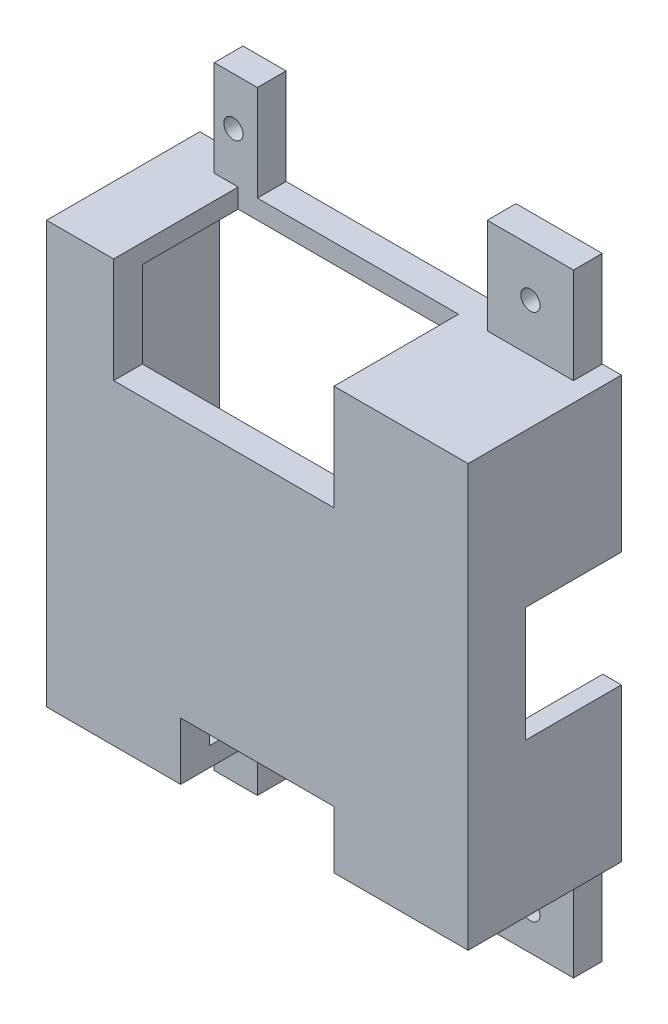
SolidWorks part; units mm, degrees
ref_plane "Front Plane" through (0, 0, 0) normal (0, 0, 1) x (1, 0, 0)
ref_plane "Top Plane" through (0, 0, 0) normal (0, 1, 0) x (1, 0, 0)
ref_plane "Right Plane" through (0, 0, 0) normal (1, 0, 0) x (0, 0, -1)
sketch "Sketch1" plane through (0, 0, 0) normal (0, 0, 1) x (1, 0, 0)
  line L0 (0, 0) -> (44, 0)
  line L1 (44, 0) -> (44, 44)
  line L2 (44, 44) -> (0, 44)
  line L3 (0, 44) -> (0, 0)
  dimension "D1" = 44
  dimension "D2" = 44
extrude "Boss-Extrude1" add sketch "Sketch1" along normal blind 16
sketch "Sketch3" plane through (0, 0, 0) normal (0, 0, -1) x (-1, 0, 0)
  line L1 (-42.0638, 42) -> (-2.0638, 42)
  line L2 (-42.0638, 42) -> (-42.0638, 2)
  line L3 (-42.0638, 2) -> (-2.0638, 2)
  line L4 (-2.0638, 42) -> (-2.0638, 2)
  dimension "D1" = 40
  dimension "D2" = 40
  dimension "D3" = 2
  dimension "D4" = 2
  dimension "D5" = 2
  dimension "D6" = 2
extrude "Cut-Extrude1" cut sketch "Sketch3" against normal blind 13
ref_plane "Plane1" through (0, 44, 16) normal (-1, 0, 0) x (0, 0, 1)
sketch "Sketch5" plane through (0, 0, 16) normal (0, 0, 1) x (1, 0, 0)
  line L0 (0, 44) -> (0, 0) construction
  line L1 (7, 44) -> (30, 44)
  line L2 (7, 44) -> (7, 33)
  line L3 (7, 33) -> (30, 33)
  line L4 (30, 44) -> (30, 33)
  point P10 (32.1603, 33.7213)
  dimension "D1" = 0
  dimension "D2" = 7
  dimension "D3" = 14
  dimension "D4" = 11
extrude "Cut-Extrude2" cut sketch "Sketch5" against normal blind 13
sketch "Sketch6" plane through (0, 0, 16) normal (0, 0, 1) x (1, 0, 0)
  line L0 (0, 0) -> (44, 0) construction
  line L1 (14, 6) -> (30, 6)
  line L2 (14, 6) -> (14, 0)
  line L3 (14, 0) -> (30, 0)
  line L4 (30, 6) -> (30, 0)
  dimension "D1" = 14
  dimension "D2" = 14
  dimension "D3" = 6
extrude "Cut-Extrude3" cut sketch "Sketch6" against normal blind 10
sketch "Sketch7" plane through (44, 0, 0) normal (1, 0, 0) x (0, 0, -1)
  line L0 (0, 0) -> (0, 44) construction
  line L1 (0, 16) -> (-10, 16)
  line L2 (0, 16) -> (0, 28)
  line L3 (0, 28) -> (-10, 28)
  line L4 (-10, 16) -> (-10, 28)
  dimension "D1" = 16
  dimension "D2" = 16
  dimension "D3" = 10
extrude "Cut-Extrude4" cut sketch "Sketch7" against normal blind 5
sketch "Sketch8" plane through (0, 0, 0) normal (0, -1, 0) x (-1, 0, 0)
  line L0 (0, 0) -> (-44, 0) construction
  line L1 (-4.5, -3) -> (-9, -3)
  line L2 (-4.5, -3) -> (-4.5, 0)
  line L3 (-4.5, 0) -> (-9, 0)
  line L4 (-9, -3) -> (-9, 0)
  line L6 (-33, -3) -> (-42, -3)
  line L7 (-33, -3) -> (-33, 0)
  line L8 (-33, 0) -> (-42, 0)
  line L9 (-42, -3) -> (-42, 0)
  dimension "D1" = 3
  dimension "D2" = 24
  dimension "D3" = 4.5
  dimension "D4" = 9
  dimension "D5" = 3
  dimension "D6" = 9
extrude "Boss-Extrude2" add sketch "Sketch8" along normal blind 10
sketch "Sketch9" plane through (0, 0, 3) normal (0, 0, 1) x (1, 0, 0)
  line L0 (33, -10) -> (33, 0) construction
  circle A0 centre (6.5, -6.0773) radius 1
  circle A1 centre (37.5, -6.0773) radius 1
  dimension "D2" = 2
  dimension "D3" = 2
  dimension "D1" = 31
  dimension "D4" = 4.5
extrude "Cut-Extrude5" cut sketch "Sketch9" against normal blind 10
sketch "Sketch10" plane through (0, 44, 0) normal (0, 1, 0) x (1, 0, 0)
  line L0 (44, 0) -> (0, 0) construction
  line L1 (42, 0) -> (33, 0)
  line L2 (42, 0) -> (42, -3)
  line L3 (42, -3) -> (33, -3)
  line L4 (33, 0) -> (33, -3)
  line L6 (9, 0) -> (4.5, 0)
  line L7 (9, 0) -> (9, -3)
  line L8 (9, -3) -> (4.5, -3)
  line L9 (4.5, 0) -> (4.5, -3)
  dimension "D1" = 3
  dimension "D2" = 3
  dimension "D3" = 9
  dimension "D4" = 24
  dimension "D5" = 4.5
  dimension "D6" = 9
extrude "Boss-Extrude3" add sketch "Sketch10" along normal blind 10
sketch "Sketch11" plane through (0, 0, 3) normal (0, 0, 1) x (1, 0, 0)
  line L0 (42, 54) -> (42, 44) construction
  circle A0 centre (37.5, 49.0313) radius 1
  circle A1 centre (6.5, 49.0313) radius 1
  point P6 (0, 0)
  point P7 (0, 0)
  dimension "D3" = 2
  dimension "D4" = 2
  dimension "D1" = 31
  dimension "D2" = 4.5
extrude "Cut-Extrude6" cut sketch "Sketch11" against normal blind 10
